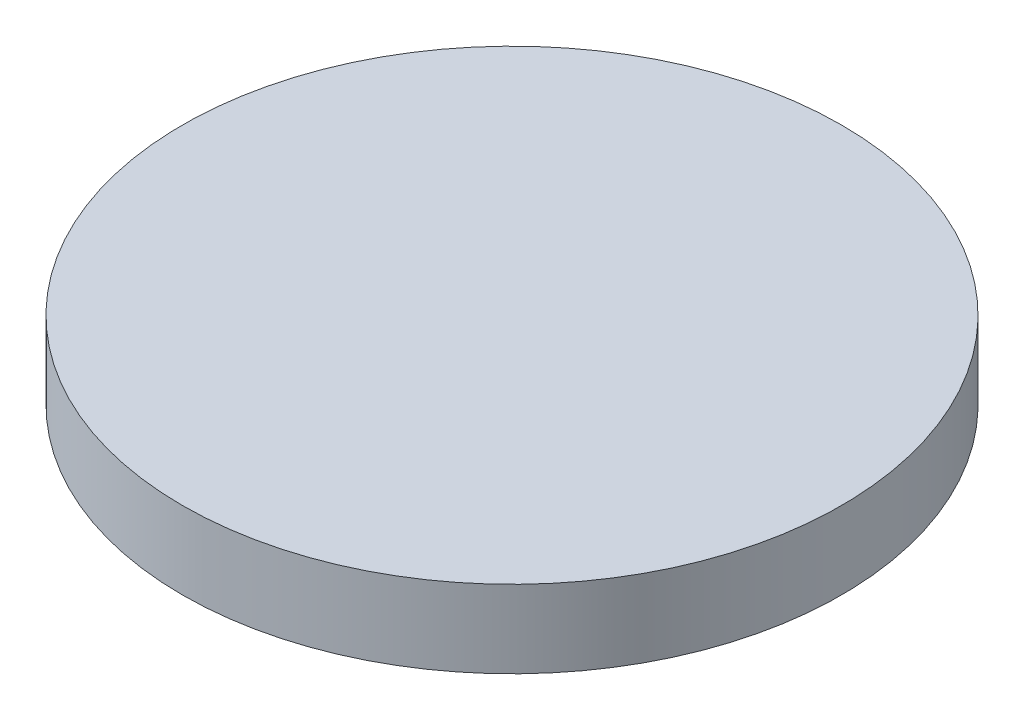
SolidWorks part; units mm, degrees
ref_plane "Alzado" through (0, 0, 0) normal (0, 0, 1) x (1, 0, 0)
ref_plane "Planta" through (0, 0, 0) normal (0, 1, 0) x (1, 0, 0)
ref_plane "Vista lateral" through (0, 0, 0) normal (1, 0, 0) x (0, 0, -1)
sketch "Sketch1" plane through (0, 0, 0) normal (0, 1, 0) x (1, 0, 0)
  circle A0 centre (0, 0) radius 21.2578
extrude "Boss-Extrude1" add sketch "Sketch1" along normal blind 5
